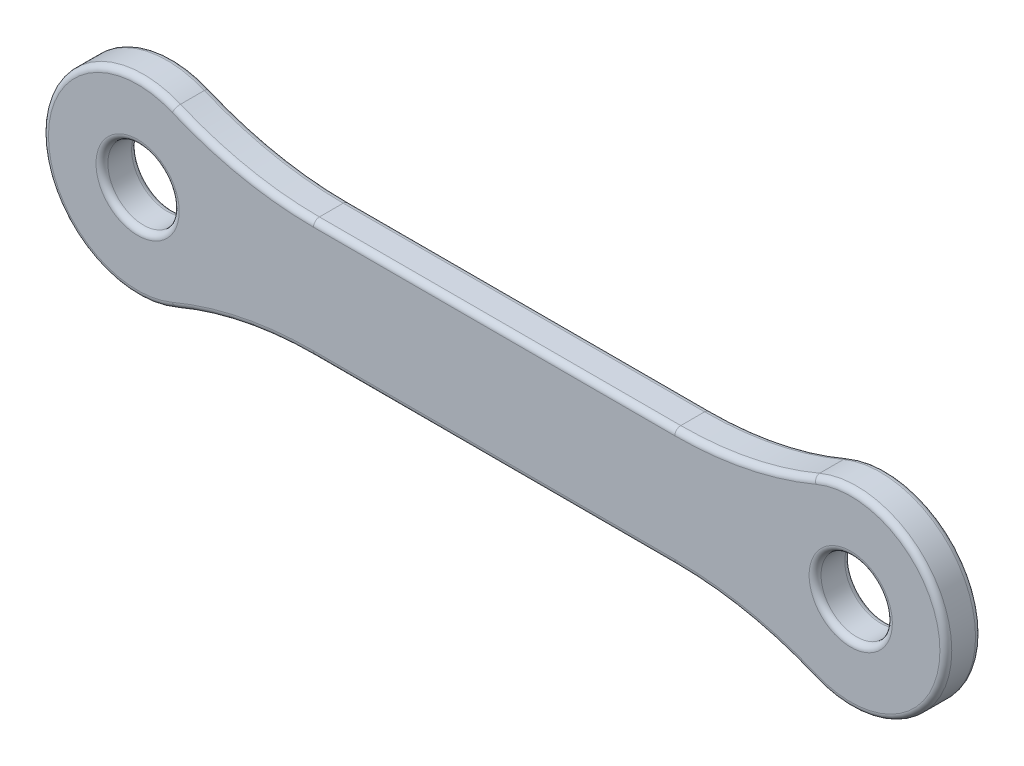
SolidWorks part; units mm, degrees
material "AR-M2"
ref_plane "正面" through (0, 0, 0) normal (0, 0, 1) x (1, 0, 0)
ref_plane "平面" through (0, 0, 0) normal (0, 1, 0) x (1, 0, 0)
ref_plane "右側面" through (0, 0, 0) normal (1, 0, 0) x (0, 0, -1)
sketch "ｽｹｯﾁ1" plane through (0, 0, 0) normal (0, 0, 1) x (1, 0, 0)
  line L0 (0, 0) -> (60, 0) construction
  line L1 (0, 5) -> (60, 5)
  line L2 (60, -5) -> (0, -5)
  arc A0 (0, 5) -> (0, -5) centre (0, 0) ccw
  arc A1 (60, -5) -> (60, 5) centre (60, 0) ccw
  circle A2 centre (0, 0) radius 3
  circle A3 centre (60, 0) radius 3
  dimension "D2" = 10
  dimension "D3" = 10
  dimension "D4" = 6
  dimension "D1" = 60
extrude "ﾎﾞｽ - 押し出し1" add sketch "ｽｹｯﾁ1" along normal blind 3
sketch "ｽｹｯﾁ2" plane through (0, 0, 0) normal (0, 0, -1) x (-1, 0, 0)
  circle A0 centre (0, 0) radius 3
  dimension "D1" = 6
extrude "ｶｯﾄ - 押し出し1" [suppressed] cut sketch "ｽｹｯﾁ2" against normal through all
sketch "ｽｹｯﾁ3" plane through (0, 0, 3) normal (0, 0, 1) x (1, 0, 0)
  line L0 (30, 5) -> (30, -5) construction
  line L1 (60, 5) -> (0, 5) construction
  line L2 (0, -5) -> (60, -5) construction
  circle A0 centre (0, 0) radius 8
  circle A1 centre (0, 0) radius 3 construction
  circle A2 centre (0, 0) radius 3
  circle A3 centre (60, 0) radius 3
  circle A4 centre (60, 0) radius 8
  dimension "D1" = 5
  dimension "D2" = 16
extrude "ﾎﾞｽ - 押し出し2" add sketch "ｽｹｯﾁ3" against normal up to surface (3 mm away) up to face at (30, 0, 0)
fillet "ﾌｨﾚｯﾄ2" radius 30 4 edges at (6.245, -5, 1.5) (53.755, -5, 1.5) (53.755, 5, 1.5) (6.245, 5, 1.5)
fillet "ﾌｨﾚｯﾄ1" radius 0.5 20 edges at (63, 0, 0) (30, -5, 0) (30, 5, 0) (3, 0, 0) (63, 0, 3) (30, 5, 3) (30, -5, 3) (3, 0, 3) (8.8383, 5.5981, 0) (-8, 0, 0) (-8, 0, 3) (8.8383, -5.5981, 0) (51.1617, -5.5981, 0) (68, 0, 3) (68, 0, 0) (51.1617, 5.5981, 0) (8.8383, 5.5981, 3) (51.1617, 5.5981, 3) (51.1617, -5.5981, 3) (8.8383, -5.5981, 3)
